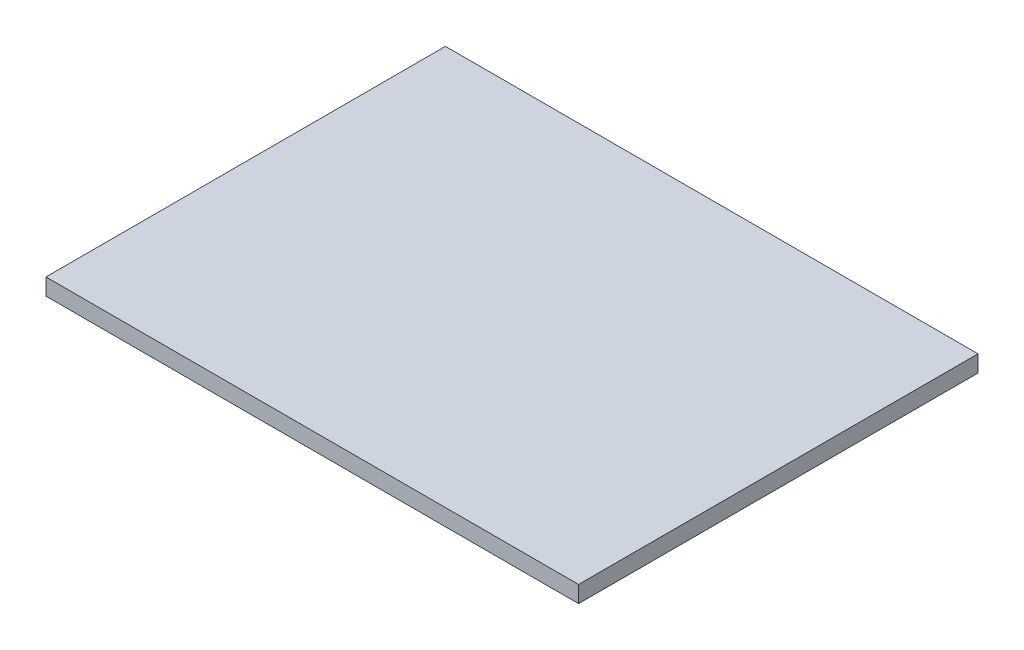
SolidWorks part; units mm, degrees
material "Brass"
ref_plane "Front Plane" through (0, 0, 0) normal (0, 0, 1) x (1, 0, 0)
ref_plane "Top Plane" through (0, 0, 0) normal (0, 1, 0) x (1, 0, 0)
ref_plane "Right Plane" through (0, 0, 0) normal (1, 0, 0) x (0, 0, -1)
sketch "Sketch1" plane through (0, 0, 0) normal (0, 1, 0) x (1, 0, 0)
  line L1 (-101.6, -76.2) -> (101.6, -76.2)
  line L2 (-101.6, -76.2) -> (-101.6, 76.2)
  line L3 (-101.6, 76.2) -> (101.6, 76.2)
  line L4 (101.6, -76.2) -> (101.6, 76.2)
  line L5 (-101.6, -76.2) -> (101.6, 76.2) construction
  line L6 (-101.6, 76.2) -> (101.6, -76.2) construction
  point P0 (0, 0)
  dimension "D1" = 203.2
  dimension "D2" = 152.4
extrude "Boss-Extrude1" add sketch "Sketch1" along normal blind 6.35
